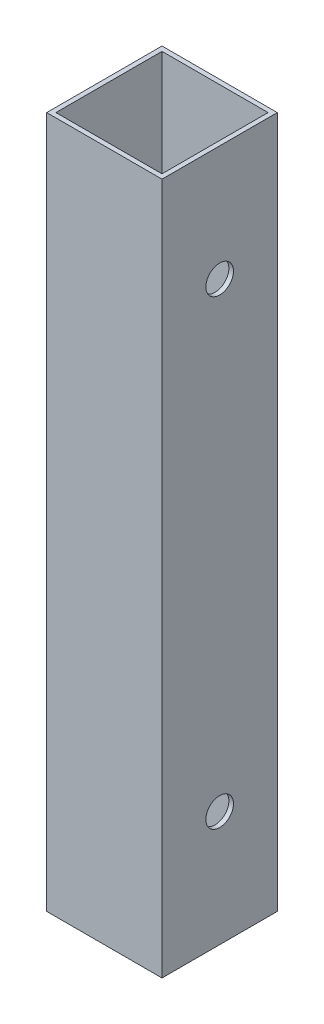
SolidWorks part; units mm, degrees
ref_plane "Front Plane" through (0, 0, 0) normal (0, 0, 1) x (1, 0, 0)
ref_plane "Top Plane" through (0, 0, 0) normal (0, 1, 0) x (1, 0, 0)
ref_plane "Right Plane" through (0, 0, 0) normal (1, 0, 0) x (0, 0, -1)
sketch "Sketch1" plane through (0, 0, 0) normal (0, 1, 0) x (1, 0, 0)
  line L0 (-11.5, -11.5) -> (11.5, -11.5)
  line L1 (-12.5, -12.5) -> (12.5, -12.5)
  line L2 (-12.5, -12.5) -> (-12.5, 12.5)
  line L3 (-12.5, 12.5) -> (12.5, 12.5)
  line L4 (12.5, -12.5) -> (12.5, 12.5)
  line L5 (-12.5, -12.5) -> (12.5, 12.5) construction
  line L6 (-12.5, 12.5) -> (12.5, -12.5) construction
  line L7 (11.5, -11.5) -> (11.5, 11.5)
  line L8 (-11.5, 11.5) -> (11.5, 11.5)
  line L9 (-11.5, -11.5) -> (-11.5, 11.5)
  point P0 (0, 0)
  dimension "D2" = 25
  dimension "D1" = 1
extrude "Boss-Extrude1" add sketch "Sketch1" along normal blind 150
sketch "Sketch2" plane through (12.5, 0, 0) normal (1, 0, 0) x (0, 0, -1)
  line L0 (0, 0) -> (0, 150) construction
  line L1 (-12.5, 150) -> (12.5, 150) construction
  circle A0 centre (0, 125) radius 3
  circle A1 centre (0, 25) radius 3
  dimension "D1" = 100
  dimension "D3" = 6
  dimension "D2" = 25
extrude "Cut-Extrude1" cut sketch "Sketch2" against normal through all
